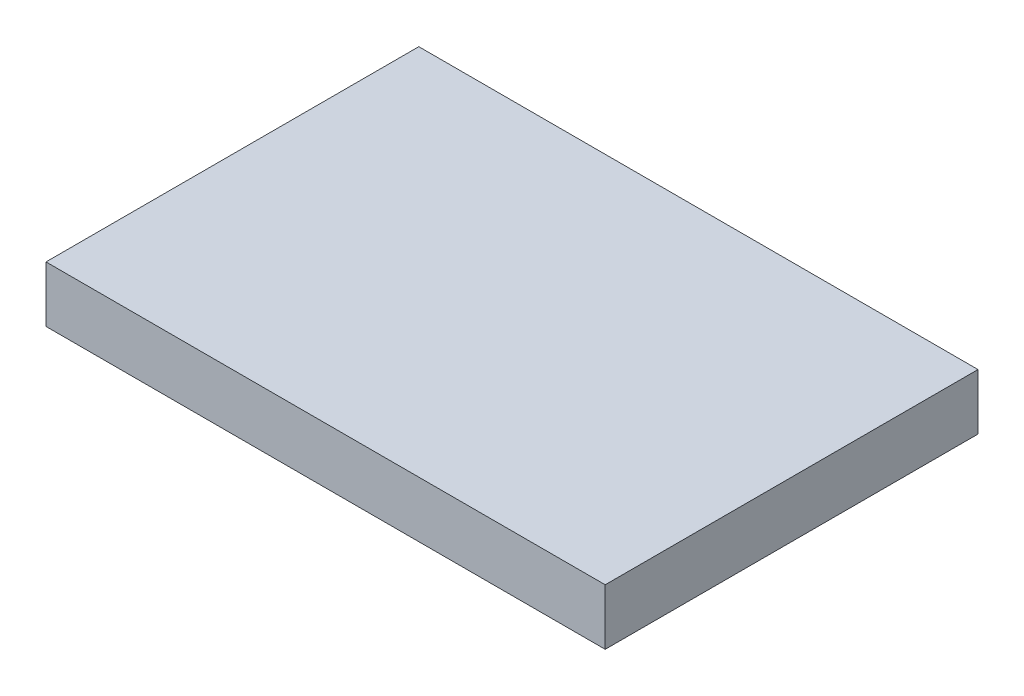
SolidWorks part; units mm, degrees
ref_plane "Front Plane" through (0, 0, 0) normal (0, 0, 1) x (1, 0, 0)
ref_plane "Top Plane" through (0, 0, 0) normal (0, 1, 0) x (1, 0, 0)
ref_plane "Right Plane" through (0, 0, 0) normal (1, 0, 0) x (0, 0, -1)
sketch "Sketch1" plane through (0, 0, 0) normal (0, 1, 0) x (1, 0, 0)
  line L1 (0, 0) -> (30, 0)
  line L2 (0, 0) -> (0, 20)
  line L3 (0, 20) -> (30, 20)
  line L4 (30, 0) -> (30, 20)
  dimension "D1" = 30
  dimension "D2" = 20
extrude "Boss-Extrude1" add sketch "Sketch1" along normal blind 3 contours L1 L4 L3 L2
